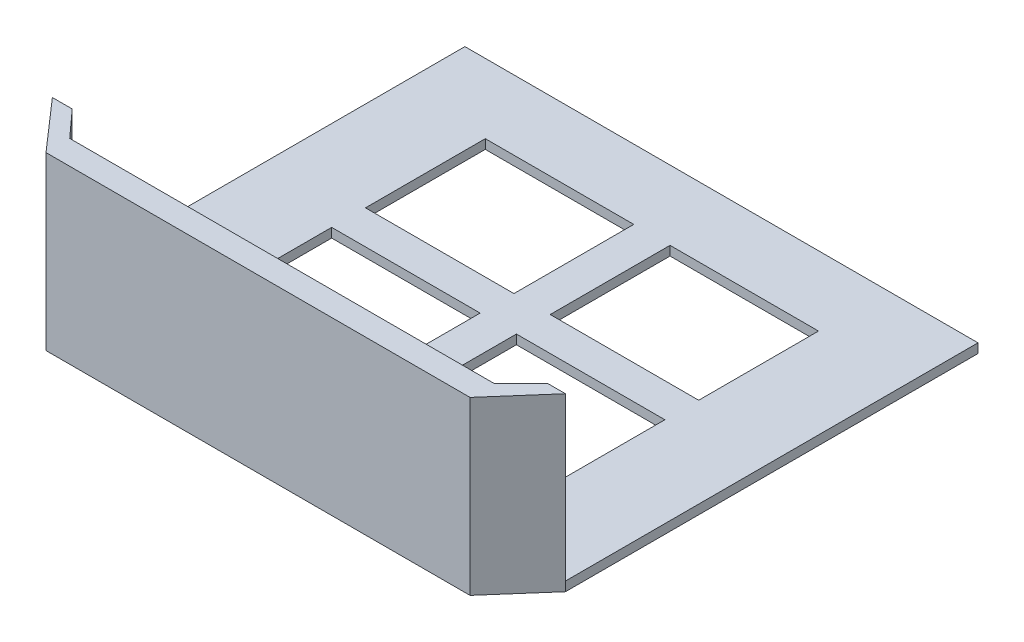
SolidWorks part; units mm, degrees
ref_plane "Plan de face" through (0, 0, 0) normal (0, 0, 1) x (1, 0, 0)
ref_plane "Plan de dessus" through (0, 0, 0) normal (0, 1, 0) x (1, 0, 0)
ref_plane "Plan de droite" through (0, 0, 0) normal (1, 0, 0) x (0, 0, -1)
sketch "Esquisse1" plane through (0, 0, 0) normal (0, 1, 0) x (-1, 0, 0)
  line L0 (-151.8462, 122.0879) -> (-125.4906, 152.2085)
  line L2 (-151.8462, 122.0879) -> (-151.8462, -122.0879)
  line L3 (-151.8462, -122.0879) -> (151.8462, -122.0879)
  line L4 (151.8462, 122.0879) -> (151.8462, -122.0879)
  line L7 (-125.4906, 152.2085) -> (125.4906, 152.2085)
  line L8 (125.4906, 152.2085) -> (151.8462, 122.0879)
extrude "Boss.-Extru.1" add sketch "Esquisse1" along normal blind 5.5
sketch "Esquisse2" plane through (0, 5.5, 0) normal (0, 1, 0) x (1, 0, 0)
  line L0 (-151.8462, -122.0879) -> (-140.0905, -122.0879)
  line L1 (-151.8462, -122.0879) -> (-125.4906, -152.2085)
  line L2 (-125.7349, -137.9385) -> (-140.0905, -122.0879)
  line L3 (-125.4906, -152.2085) -> (125.4906, -152.2085)
  line L4 (125.4906, -137.9385) -> (141.3412, -122.0879)
  line L5 (141.3412, -122.0879) -> (151.8462, -122.0879)
  line L6 (-125.7349, -137.9385) -> (125.4906, -137.9385)
  line L7 (125.4906, -152.2085) -> (151.8462, -122.0879)
  point P3 (-132.9127, -130.0132)
  dimension "D1" = 14.27
  dimension "D2" = 9.03
extrude "Boss.-Extru.2" add sketch "Esquisse2" along normal blind 96
sketch "Esquisse3" plane through (0, 0, 0) normal (0, -1, 0) x (1, 0, 0)
  line L1 (-98.614, -80.921) -> (98.614, -80.921)
  line L2 (-98.614, -80.921) -> (-98.614, 80.921)
  line L3 (-98.614, 80.921) -> (98.614, 80.921)
  line L4 (98.614, -80.921) -> (98.614, 80.921)
  point P0 (0, 0)
extrude "Enlèv. mat.-Extru.1" cut sketch "Esquisse3" against normal blind 37 and the other way blind 39
sketch "Esquisse4" plane through (0, 0, 0) normal (0, -1, 0) x (1, 0, 0)
  line L1 (98.614, 80.921) -> (-98.614, 80.921) construction
  line L2 (-10.7386, 80.921) -> (10.7386, 80.921)
  line L4 (-98.614, 10) -> (-98.614, -10)
  line L6 (98.614, -80.921) -> (98.614, 80.921) construction
  line L7 (98.614, -10) -> (98.614, 10)
  line L10 (-98.614, -80.921) -> (98.614, -80.921) construction
  line L11 (-10.7386, -80.921) -> (10.7386, -80.921)
  line L12 (10.7386, -80.921) -> (10.7386, -10)
  line L13 (10.7386, -10) -> (98.614, -10)
  line L14 (10.7386, 80.921) -> (10.7386, 10)
  line L15 (10.7386, 10) -> (98.614, 10)
  line L16 (-10.7386, -80.921) -> (-10.7386, -10)
  line L17 (-10.7386, -10) -> (-98.614, -10)
  line L18 (-98.614, 10) -> (-10.7386, 10)
  line L19 (-10.7386, 10) -> (-10.7386, 80.921)
  point P12 (-98.614, 0)
  point P13 (0, 80.921)
extrude "Boss.-Extru.3" add sketch "Esquisse4" against normal up to surface (5.5 mm away) up to face at (0.1258, 5.5, 65.0066)
